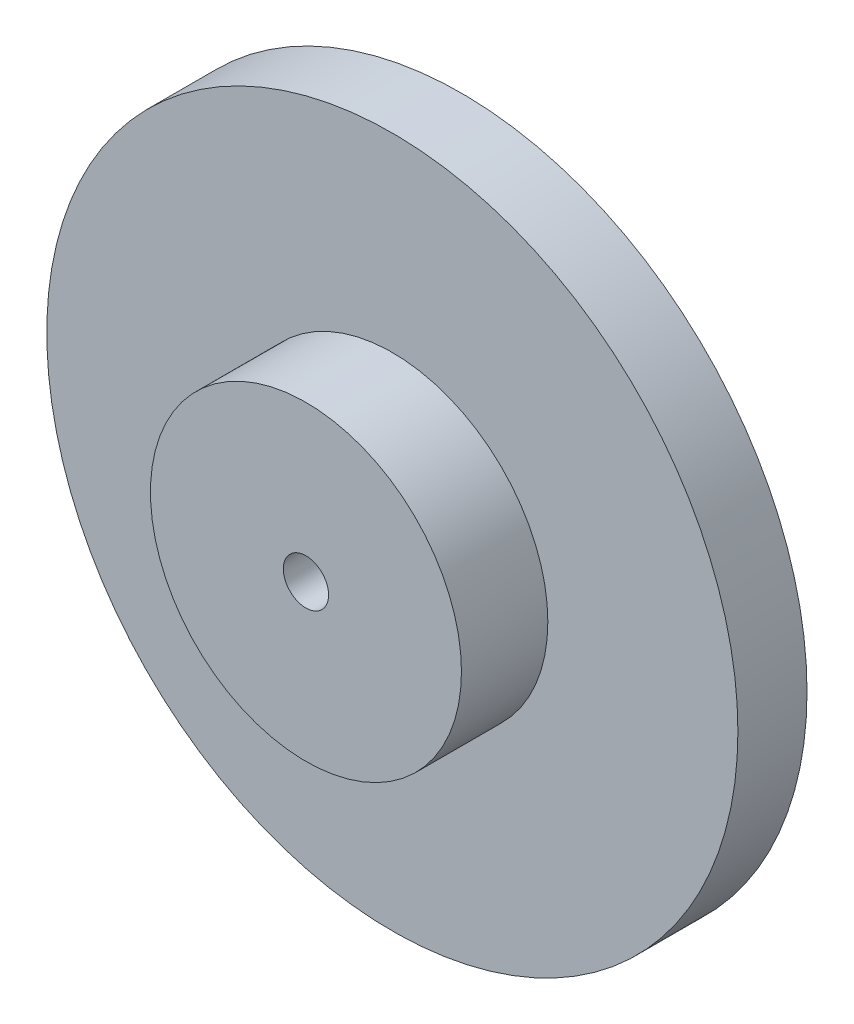
SolidWorks part; units mm, degrees
ref_plane "Front Plane" through (0, 0, 0) normal (0, 0, 1) x (1, 0, 0)
ref_plane "Top Plane" through (0, 0, 0) normal (0, 1, 0) x (1, 0, 0)
ref_plane "Right Plane" through (0, 0, 0) normal (1, 0, 0) x (0, 0, -1)
sketch "Sketch1" plane through (0, 0, 0) normal (0, 0, 1) x (1, 0, 0)
  circle A0 centre (0, 0) radius 10
extrude "Boss-Extrude1" add sketch "Sketch1" along normal blind 2
sketch "Sketch2" plane through (0, 0, 2) normal (0, 0, 1) x (1, 0, 0)
  circle A0 centre (0, 0) radius 4.5
extrude "Boss-Extrude2" add sketch "Sketch2" along normal blind 2.5
sketch "Sketch3" plane through (0, 0, 4.5) normal (0, 0, 1) x (1, 0, 0)
  circle A0 centre (0, 0) radius 0.655
extrude "Cut-Extrude1" cut sketch "Sketch3" against normal blind 15.5 contours A0
